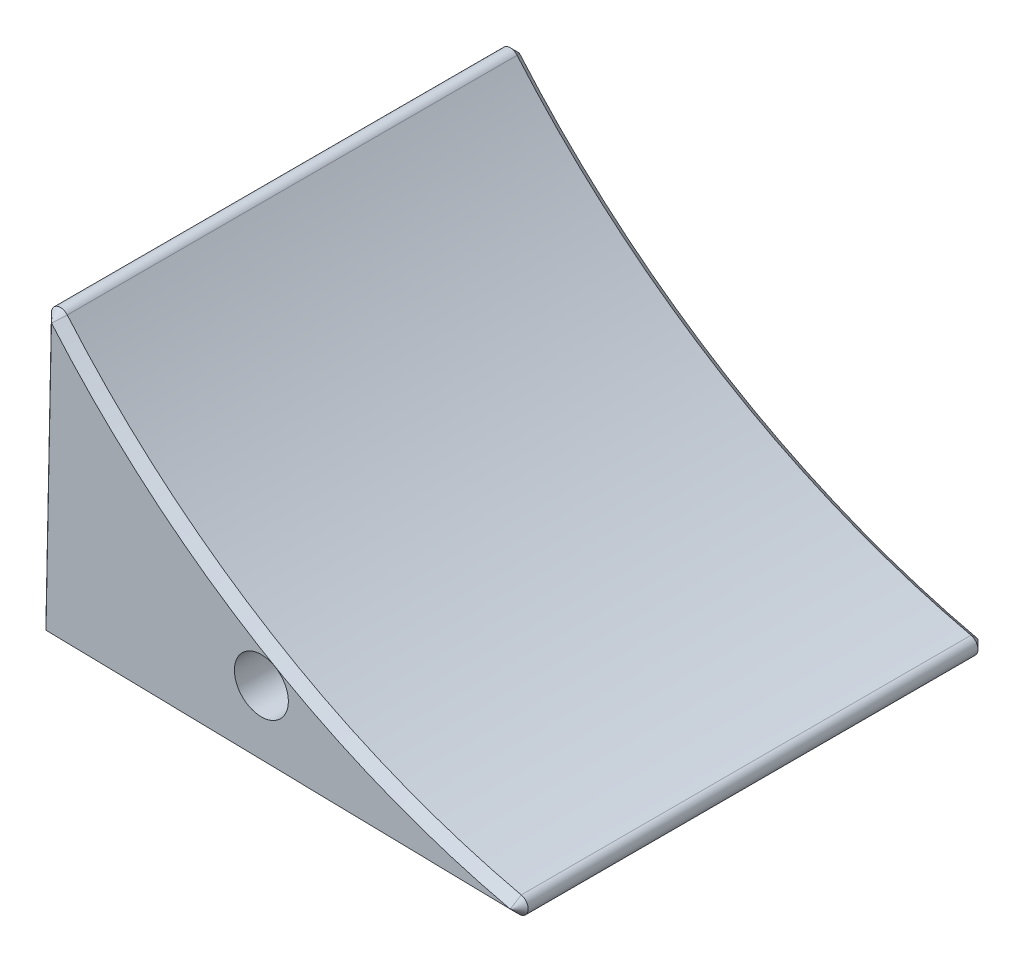
SolidWorks part; units mm, degrees
material "尼龙 101"
ref_plane "前视基准面" through (0, 0, 0) normal (0, 0, 1) x (1, 0, 0)
ref_plane "上视基准面" through (0, 0, 0) normal (0, 1, 0) x (1, 0, 0)
ref_plane "右视基准面" through (0, 0, 0) normal (1, 0, 0) x (0, 0, -1)
sketch "草图1" plane through (0, 0, 0) normal (0, 0, 1) x (1, 0, 0)
  line L0 (-212.1807, 127.0299) -> (-212.521, 110.2493)
  line L1 (-212.521, 110.2493) -> (-176.5284, 109.5194)
  line L5 (-212.5615, 108.2497) -> (-212.2402, 124.0969) construction
  line L6 (-143.5352, 108.8504) -> (-209.5216, 110.1885) construction
  arc A0 (-212.1807, 127.0299) -> (-176.5284, 109.5194) centre (-175.5755, 156.5098) ccw
  circle A1 centre (-175.5755, 156.5098) radius 47 construction
extrude "凸台-拉伸1" add sketch "草图1" along normal up to surface (26 mm away)
sketch "草图2" plane through (0, 0, 0) normal (0, 0, -1) x (-1, 0, 0)
  circle A0 centre (200.0412, 114.0527) radius 1.5 construction
  circle A1 centre (200.0412, 114.0527) radius 1.5
extrude "切除-拉伸1" cut sketch "草图2" against normal through all both and the other way through all
fillet "圆角1" radius 0.5 3 edges at (-176.5284, 109.5194, 13) (-212.1807, 127.0299, 13) (-212.521, 110.2493, 13)
chamfer "倒角1" distance 0.5 angle 45 12 edges at (-211.8762, 126.1474, 26) (-212.3594, 118.2179, 26) (-199.9452, 116.3212, 26) (-212.3716, 110.3927, 26) (-185.7154, 110.1545, 26) (-199.1214, 109.9776, 26) (-211.8762, 126.1474, 0) (-212.3594, 118.2179, 0) (-199.9452, 116.3212, 0) (-212.3716, 110.3927, 0) (-185.7154, 110.1545, 0) (-199.1214, 109.9776, 0)
